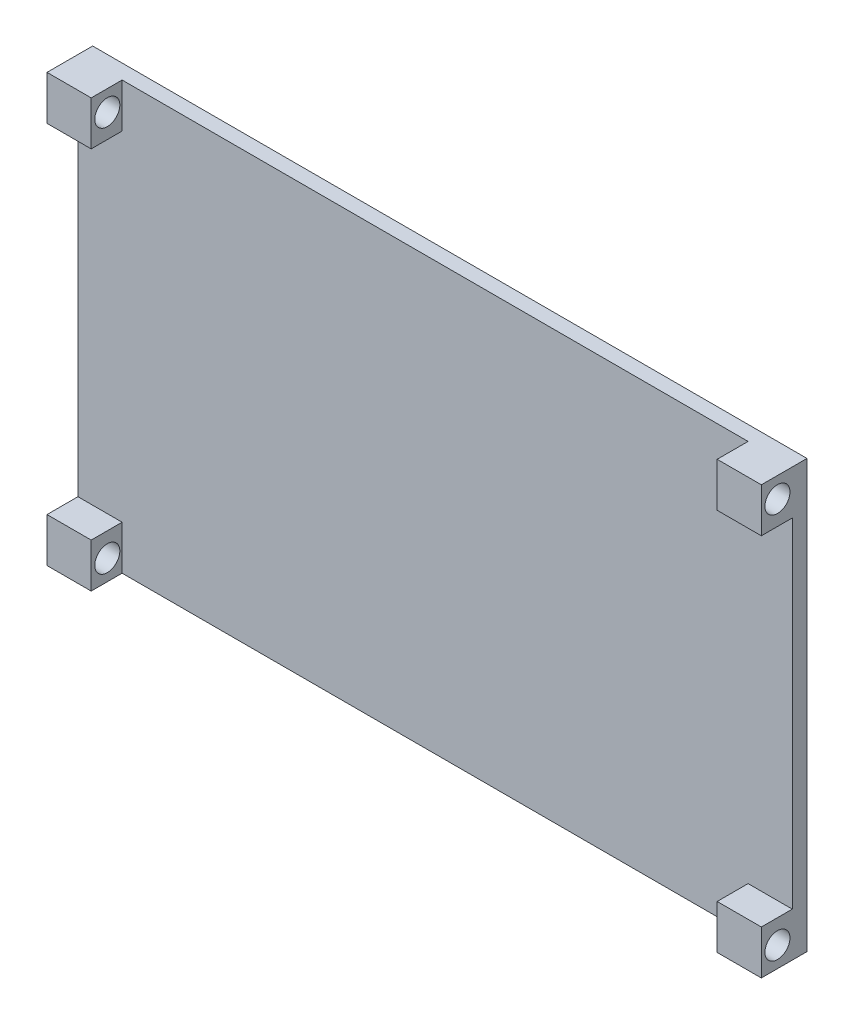
SolidWorks part; units mm, degrees
ref_plane "Alzado" through (0, 0, 0) normal (0, 0, 1) x (1, 0, 0)
ref_plane "Planta" through (0, 0, 0) normal (0, 1, 0) x (1, 0, 0)
ref_plane "Vista lateral" through (0, 0, 0) normal (1, 0, 0) x (0, 0, -1)
sketch "Croquis1" plane through (0, 0, 0) normal (0, 0, 1) x (1, 0, 0)
  line L1 (-48.5, 29) -> (48.5, 29)
  line L2 (-48.5, 29) -> (-48.5, -29)
  line L3 (-48.5, -29) -> (48.5, -29)
  line L4 (48.5, 29) -> (48.5, -29)
  line L5 (-48.5, 29) -> (48.5, -29) construction
  line L6 (-48.5, -29) -> (48.5, 29) construction
  point P0 (0, 0)
  dimension "D1" = 97
  dimension "D2" = 58
extrude "Saliente-Extruir1" add sketch "Croquis1" against normal blind 2
sketch "Croquis2" plane through (0, 0, 0) normal (0, 0, 1) x (1, 0, 0)
  line L0 (0, 29) -> (0, -29) construction
  line L1 (-48.5, 29) -> (-42.5, 29)
  line L2 (-48.5, 29) -> (-48.5, 23)
  line L3 (-48.5, 23) -> (-42.5, 23)
  line L4 (-42.5, 29) -> (-42.5, 23)
  line L5 (48.5, 29) -> (-48.5, 29) construction
  line L6 (-48.5, -29) -> (48.5, -29) construction
  line L7 (-48.5, 0) -> (48.5, 0) construction
  line L8 (-48.5, 29) -> (-48.5, -29) construction
  line L9 (48.5, -29) -> (48.5, 29) construction
  line L10 (-48.5, -23) -> (-42.5, -23)
  line L11 (-42.5, -29) -> (-42.5, -23)
  line L12 (-48.5, -29) -> (-42.5, -29)
  line L13 (-48.5, -29) -> (-48.5, -23)
  line L14 (48.5, -29) -> (48.5, -23)
  line L15 (48.5, -29) -> (42.5, -29)
  line L16 (42.5, -29) -> (42.5, -23)
  line L17 (48.5, -23) -> (42.5, -23)
  line L18 (48.5, 23) -> (42.5, 23)
  line L19 (42.5, 29) -> (42.5, 23)
  line L20 (48.5, 29) -> (42.5, 29)
  line L21 (48.5, 29) -> (48.5, 23)
  dimension "D1" = 6
  dimension "D2" = 6
extrude "Saliente-Extruir2" add sketch "Croquis2" along normal blind 4.2
sketch "Croquis3" plane through (-48.5, 0, 0) normal (-1, 0, 0) x (0, 0, 1)
  line L0 (4.2, 26) -> (-2, 26.6374) construction
  line L2 (-2, 29) -> (-2, -29) construction
  line L3 (0, 0) -> (-2, 0) construction
  line L4 (4.2, 29) -> (4.2, 23) construction
  circle A0 centre (2.0115, 26.225) radius 1.7
  circle A1 centre (2.0115, -26.225) radius 1.7
  dimension "D1" = 3.4
  dimension "D3" = 52.45
  dimension "D2" = 2.2
extrude "Cortar-Extruir1" cut sketch "Croquis3" against normal through all
